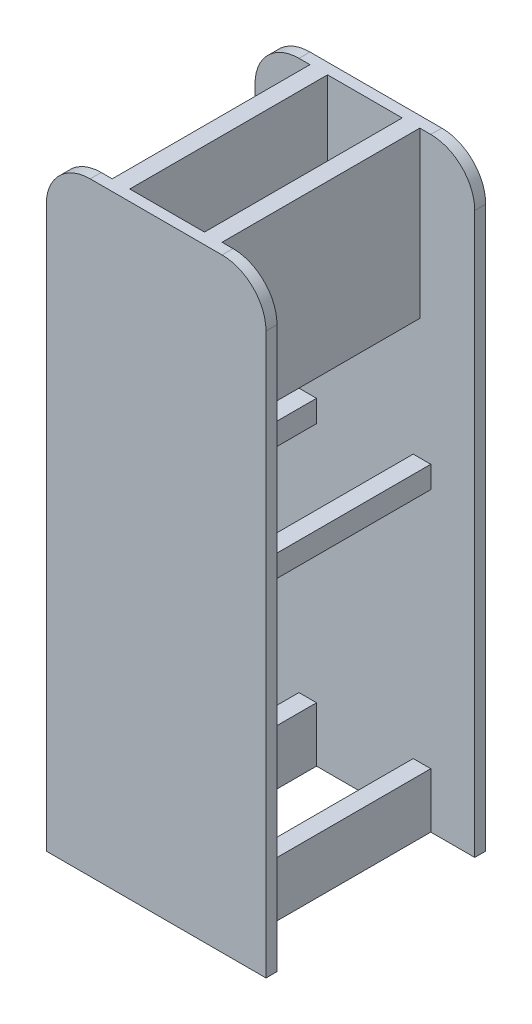
SolidWorks part; units mm, degrees
ref_plane "정면" through (0, 0, 0) normal (0, 0, 1) x (1, 0, 0)
ref_plane "윗면" through (0, 0, 0) normal (0, 1, 0) x (1, 0, 0)
ref_plane "우측면" through (0, 0, 0) normal (1, 0, 0) x (0, 0, -1)
sketch "스케치1" plane through (0, 0, 0) normal (0, 0, 1) x (1, 0, 0)
  line L1 (0, 0) -> (200, 0)
  line L2 (0, 0) -> (0, 550)
  line L3 (0, 550) -> (200, 550)
  line L4 (200, 0) -> (200, 550)
  dimension "D1" = 200
  dimension "D2" = 550
extrude "보스-돌출2" add sketch "스케치1" along normal blind 10
fillet "필렛2" radius 40 2 edges at (200, 550, 5) (0, 550, 5)
sketch "스케치2" plane through (0, 0, 10) normal (0, 0, 1) x (1, 0, 0)
  line L5 (0, 0) -> (200, 0) construction
  line L6 (144, 0) -> (160, 0)
  line L7 (144, 0) -> (144, 50)
  line L8 (144, 50) -> (160, 50)
  line L9 (160, 0) -> (160, 50)
  line L11 (144, 290) -> (160, 290)
  line L12 (144, 290) -> (144, 270)
  line L13 (144, 270) -> (160, 270)
  line L14 (160, 290) -> (160, 270)
  line L15 (160, 550) -> (40, 550) construction
  line L16 (134, 550) -> (150, 550)
  line L17 (134, 550) -> (134, 400)
  line L18 (134, 400) -> (150, 400)
  line L19 (150, 550) -> (150, 400)
  line L20 (200, 0) -> (200, 510) construction
  line L21 (100, 550) -> (100, 632.3056) construction
  line L22 (160, 550) -> (40, 550) construction
  line L23 (56, 50) -> (40, 50)
  line L24 (40, 0) -> (40, 50)
  line L25 (56, 0) -> (40, 0)
  line L26 (56, 0) -> (56, 50)
  line L27 (40, 290) -> (40, 270)
  line L28 (56, 270) -> (40, 270)
  line L29 (56, 290) -> (56, 270)
  line L30 (56, 290) -> (40, 290)
  line L31 (66, 400) -> (50, 400)
  line L32 (50, 550) -> (50, 400)
  line L33 (66, 550) -> (66, 400)
  line L34 (66, 550) -> (50, 550)
  dimension "D1" = 16
  dimension "D2" = 150
  dimension "D3" = 50
  dimension "D4" = 16
  dimension "D5" = 20
  dimension "D6" = 40
  dimension "D7" = 260
  dimension "D8" = 40
  dimension "D9" = 16
  dimension "D10" = 50
extrude "보스-돌출4" add sketch "스케치2" along normal blind 90
mirror "대칭 복사26" about plane through (0, 0, 100) normal (0, 0, -1) of "보스-돌출2", "보스-돌출4"
sketch "스케치3" plane through (0, 0, 190) normal (0, 0, 1) x (1, 0, 0)
  line L1 (0, 0) -> (200, 0)
  line L2 (0, 0) -> (0, 550)
  line L3 (0, 550) -> (200, 550)
  line L4 (200, 0) -> (200, 550)
  dimension "D1" = 200
  dimension "D2" = 550
extrude "보스-돌출5" add sketch "스케치3" along normal blind 10
fillet "필렛5" radius 40 2 edges at (0, 550, 195) (200, 550, 195)
